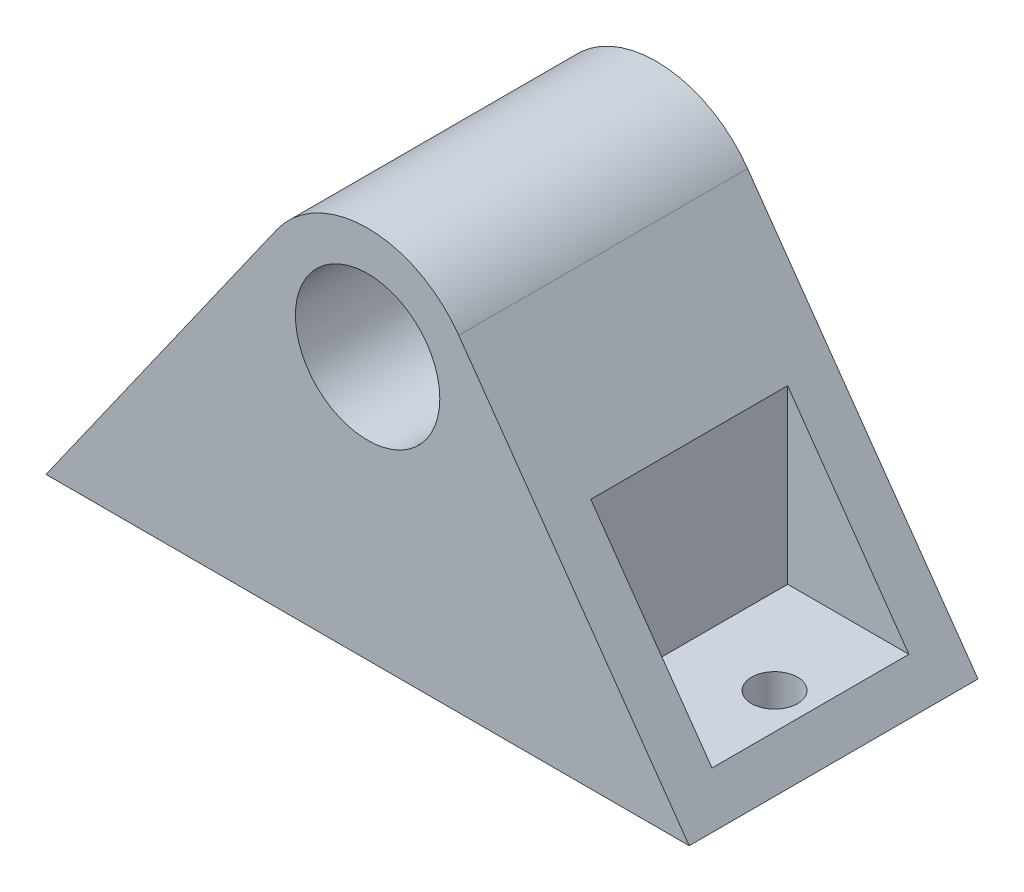
SolidWorks part; units mm, degrees
ref_plane "Front Plane" through (0, 0, 0) normal (0, 0, 1) x (1, 0, 0)
ref_plane "Top Plane" through (0, 0, 0) normal (0, 1, 0) x (1, 0, 0)
ref_plane "Right Plane" through (0, 0, 0) normal (1, 0, 0) x (0, 0, -1)
sketch "Sketch1" plane through (0, 0, 0) normal (0, 0, 1) x (1, 0, 0)
  line L0 (-24.5, 0) -> (24.5, 0)
  line L1 (0, 0) -> (0, 20) construction
  line L2 (-24.5, 0) -> (-6.9471, 24.8977)
  line L3 (24.5, 0) -> (6.9471, 24.8977)
  circle A0 centre (0, 20) radius 5.5
  circle A1 centre (0, 20) radius 8.5
  point P4 (0, 0)
  dimension "D1" = 17
  dimension "D2" = 11
  dimension "D3" = 20
  dimension "D4" = 49
extrude "Bloco" add sketch "Sketch1" along normal mid plane 22
ref_plane "Plano de Referência" through (0, 28.5, 0) normal (0, 1, 0) x (1, 0, 0)
sketch "Sketch2" plane through (0, 28.5, 0) normal (0, 1, 0) x (1, 0, 0)
  line L0 (24.5, 0) -> (-24.5, 0) construction
  line L1 (24.5, -11) -> (24.5, 11) construction
  line L2 (-24.5, -11) -> (-24.5, 11) construction
  line L3 (0, 11) -> (0, -11) construction
  line L4 (24.5, -7.5) -> (13.5, -7.5)
  line L5 (24.5, -7.5) -> (24.5, 7.5)
  line L6 (24.5, 7.5) -> (13.5, 7.5)
  line L7 (13.5, -7.5) -> (13.5, 7.5)
  line L8 (6.9471, 11) -> (-6.9471, 11) construction
  line L9 (-6.9471, -11) -> (6.9471, -11) construction
  line L10 (-24.5, 7.5) -> (-13.5, 7.5)
  line L11 (-13.5, -7.5) -> (-13.5, 7.5)
  line L12 (-24.5, -7.5) -> (-13.5, -7.5)
  line L13 (-24.5, -7.5) -> (-24.5, 7.5)
  point P10 (13.5, 0)
  dimension "D1" = 15
  dimension "D2" = 11
extrude "Rasgos Laterais" cut sketch "Sketch2" against normal blind 26
sketch "Sketch3" plane through (0, 2.5, 0) normal (0, 1, 0) x (1, 0, 0)
  line L0 (22.7375, 0) -> (13.5, 0) construction
  line L1 (22.7375, -7.5) -> (22.7375, 7.5) construction
  line L2 (13.5, 7.5) -> (13.5, -7.5) construction
  line L3 (20, 7.5) -> (20, -7.5) construction
  line L6 (22.7375, 7.5) -> (13.5, 7.5) construction
  line L7 (22.7375, -7.5) -> (13.5, -7.5) construction
  line L8 (24.5, -11) -> (24.5, 11) construction
  line L9 (0, 11) -> (0, -11) construction
  line L10 (6.9471, 11) -> (-6.9471, 11) construction
  line L11 (-6.9471, -11) -> (6.9471, -11) construction
  line L12 (-22.7375, 0) -> (-13.5, 0) construction
  line L13 (-20, 7.5) -> (-20, -7.5) construction
  circle A0 centre (20, 0) radius 1.75
  circle A1 centre (-20, 0) radius 1.75
  dimension "D2" = 3.5
  dimension "D1" = 4.5
extrude "Furos de Fixação Ø4" cut sketch "Sketch3" against normal through all
